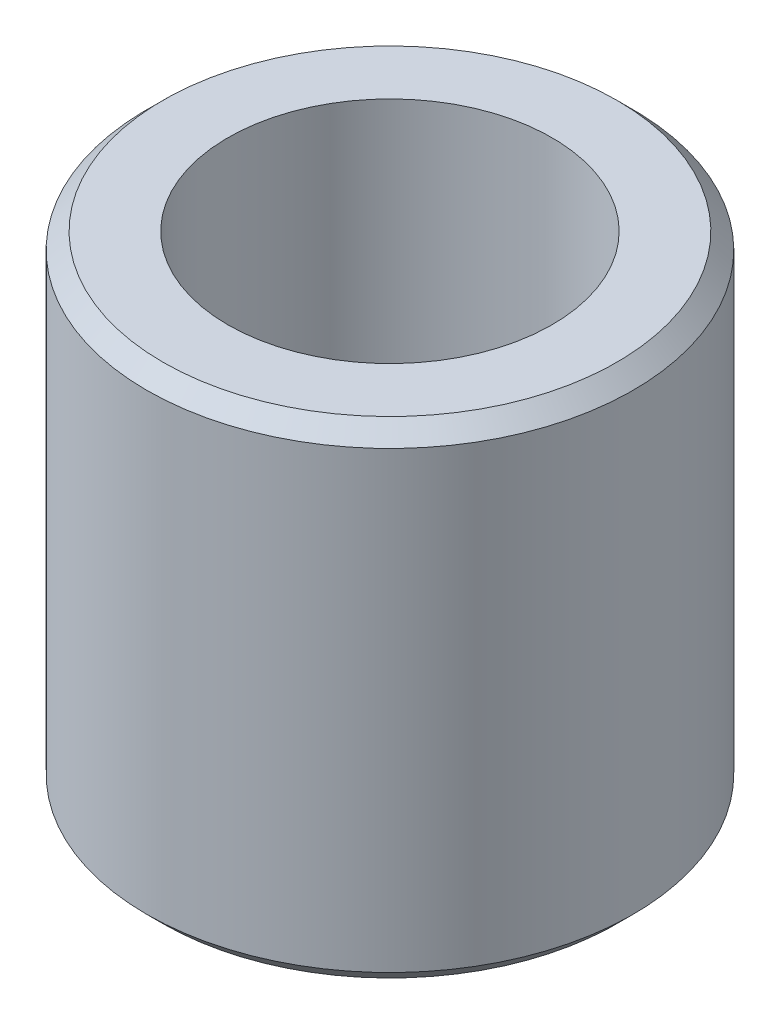
SolidWorks part; units mm, degrees
ref_plane "Front Plane" through (0, 0, 0) normal (0, 0, 1) x (1, 0, 0)
ref_plane "Top Plane" through (0, 0, 0) normal (0, 1, 0) x (1, 0, 0)
ref_plane "Right Plane" through (0, 0, 0) normal (1, 0, 0) x (0, 0, -1)
sketch "Sketch2" plane through (0, 0, 0) normal (0, 1, 0) x (1, 0, 0)
  circle A0 centre (0, 0) radius 15
  circle A1 centre (0, 0) radius 10
  dimension "D1" = 30
  dimension "D2" = 20
extrude "Boss-Extrude1" add sketch "Sketch2" along normal mid plane 30
chamfer "Chamfer1" distance 1 angle 45 2 edges at (0, -15, 15) (0, 15, 15)
